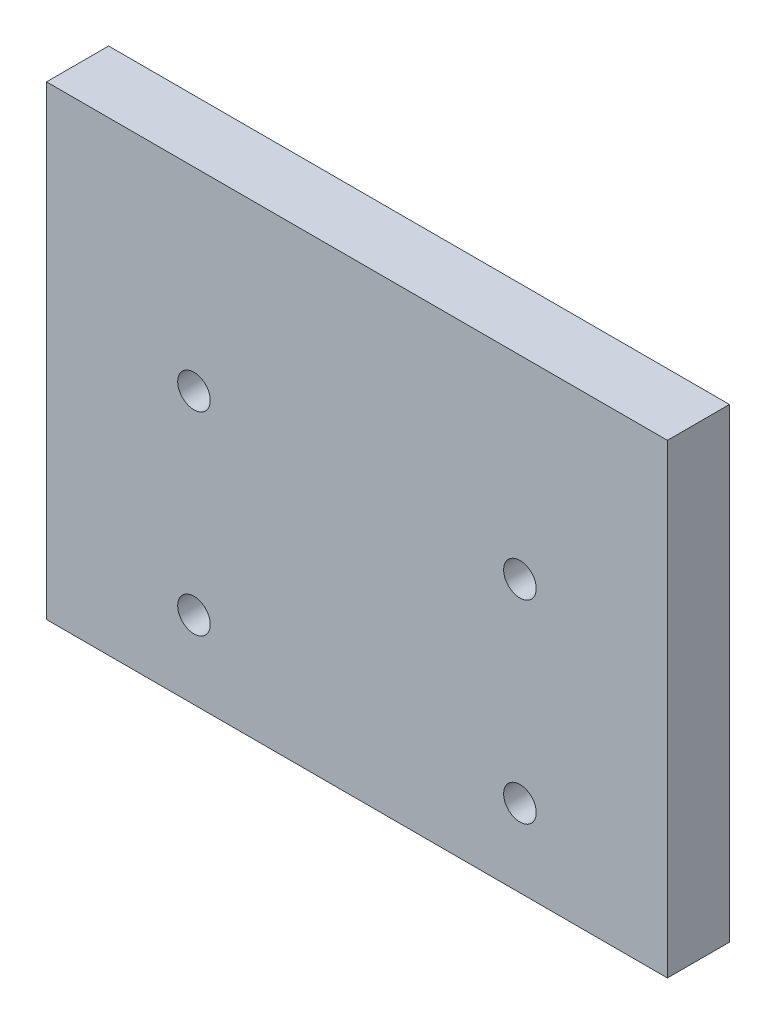
SolidWorks part; units mm, degrees
ref_plane "Front Plane" through (0, 0, 0) normal (0, 0, 1) x (1, 0, 0)
ref_plane "Top Plane" through (0, 0, 0) normal (0, 1, 0) x (1, 0, 0)
ref_plane "Right Plane" through (0, 0, 0) normal (1, 0, 0) x (0, 0, -1)
sketch "Sketch1" plane through (0, 0, 0) normal (0, 0, 1) x (1, 0, 0)
  line L1 (-20, 15) -> (20, 15)
  line L2 (-20, 15) -> (-20, -15)
  line L3 (-20, -15) -> (20, -15)
  line L4 (20, 15) -> (20, -15)
  line L5 (-20, 15) -> (20, -15) construction
  line L6 (-20, -15) -> (20, 15) construction
  point P0 (0, 0)
extrude "Boss-Extrude1" add sketch "Sketch1" along normal blind 4
sketch "Sketch2" plane through (0, 0, 0) normal (0, 0, -1) x (-1, 0, 0)
  circle A0 centre (-10.5, 2.5) radius 1.05
  circle A1 centre (10.5, 2.5) radius 1.05
  circle A2 centre (-10.5, -10) radius 1.05
  circle A3 centre (10.5, -10) radius 1.05
extrude "Cut-Extrude1" cut sketch "Sketch2" against normal through all
